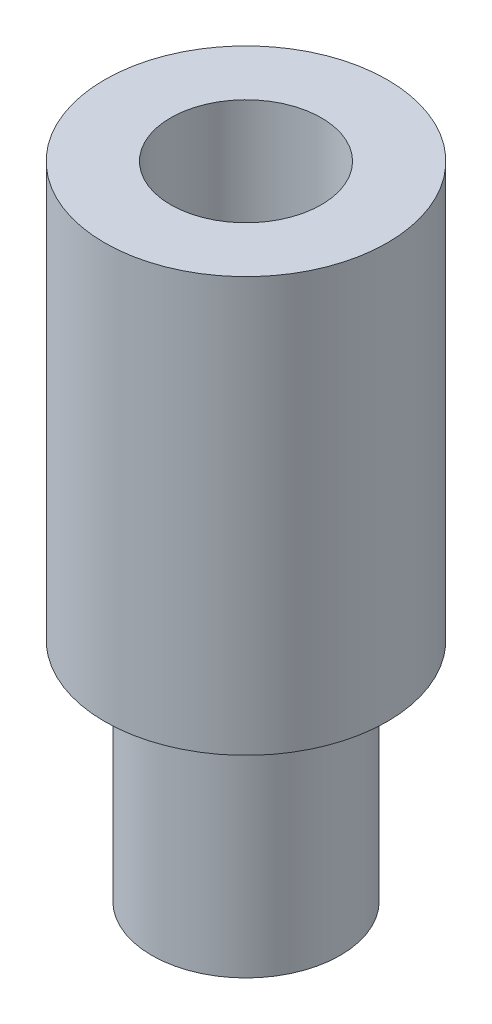
SolidWorks part; units mm, degrees
ref_plane "Front Plane" through (0, 0, 0) normal (0, 0, 1) x (1, 0, 0)
ref_plane "Top Plane" through (0, 0, 0) normal (0, 1, 0) x (1, 0, 0)
ref_plane "Right Plane" through (0, 0, 0) normal (1, 0, 0) x (0, 0, -1)
sketch "Sketch1" plane through (0, 0, 0) normal (0, 1, 0) x (1, 0, 0)
  circle A0 centre (0, 0) radius 1.15
  circle A1 centre (0, 0) radius 5
  dimension "D1" = 2.3
  dimension "D2" = 10
extrude "Boss-Extrude1" add sketch "Sketch1" along normal blind 12
sketch "Sketch2" plane through (0, 12, 0) normal (0, 1, 0) x (1, 0, 0)
  circle A0 centre (0, 0) radius 7.5
  circle A1 centre (0, 0) radius 4
  dimension "D1" = 15
  dimension "D2" = 8
extrude "Boss-Extrude2" add sketch "Sketch2" along normal blind 22
